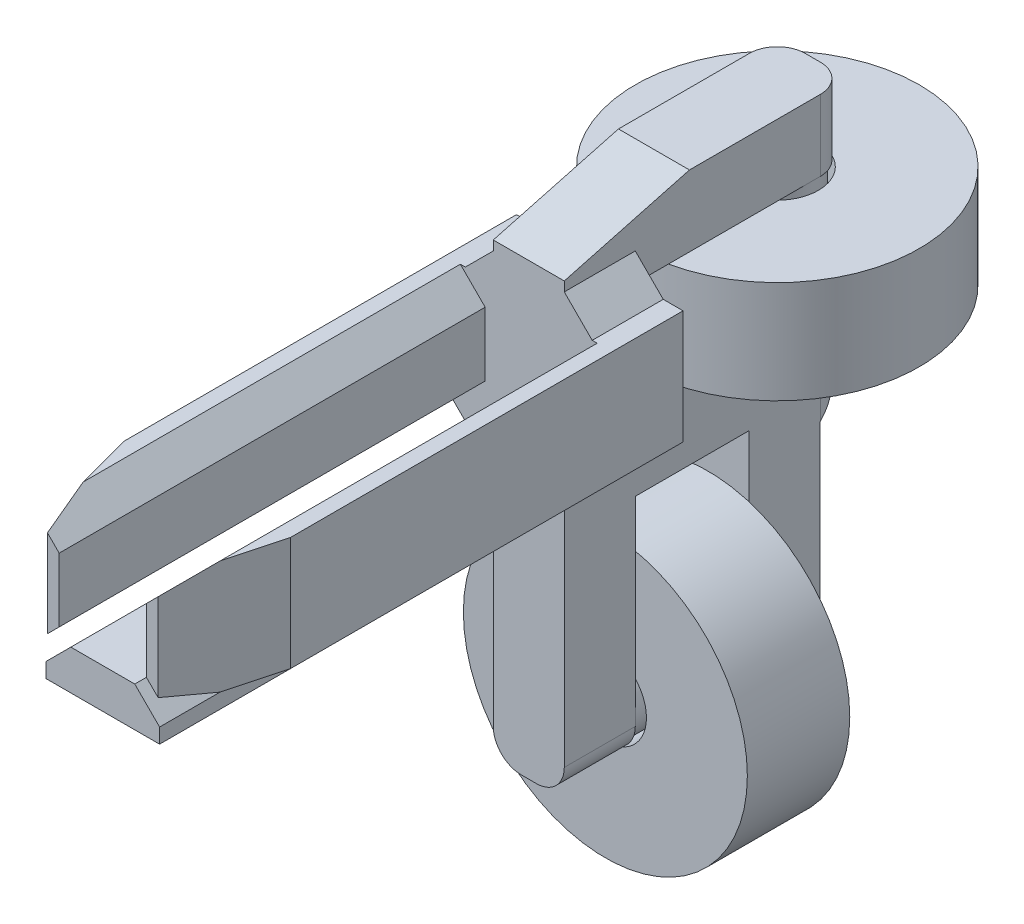
SolidWorks part; units mm, degrees
ref_plane "Front Plane" through (0, 0, 0) normal (0, 0, 1) x (1, 0, 0)
ref_plane "Top Plane" through (0, 0, 0) normal (0, 1, 0) x (1, 0, 0)
ref_plane "Right Plane" through (0, 0, 0) normal (1, 0, 0) x (0, 0, -1)
sketch "Sketch1" plane through (0, 0, 0) normal (0, 0, 1) x (1, 0, 0)
  line L1 (6.12, -5.08) -> (3.9, -2.86)
  line L2 (3.9, -2.86) -> (3.9, 2.86)
  line L3 (3.9, 2.86) -> (6.12, 5.08)
  line L5 (-6.12, -5.08) -> (-3.9, -2.86)
  line L6 (-3.9, -2.86) -> (-3.9, 2.86)
  line L7 (-3.9, 2.86) -> (-6.12, 5.08)
  line L8 (3.9, 0) -> (-3.9, 0) construction
  line L9 (0, 0) -> (-8.3021, -8.3021) construction
  line L10 (-6.12, 5.08) -> (-7.45, 5.08)
  line L12 (-6.12, -5.08) -> (-7.45, -5.08)
  line L13 (-7.45, 5.08) -> (-7.45, -5.08)
  line L14 (6.12, -5.08) -> (7.45, -5.08)
  line L16 (6.12, 5.08) -> (7.45, 5.08)
  line L17 (7.45, -5.08) -> (7.45, 5.08)
  line L18 (5.08, -7.45) -> (-5.08, -7.45)
  line L19 (-5.08, -6.12) -> (-5.08, -7.45)
  line L20 (5.08, -6.12) -> (5.08, -7.45)
  line L21 (2.86, -3.9) -> (5.08, -6.12)
  line L22 (-2.86, -3.9) -> (2.86, -3.9)
  line L23 (-5.08, -6.12) -> (-2.86, -3.9)
  dimension "D1" = 45
  dimension "D2" = 10.16
  dimension "D3" = 5.72
  dimension "D5" = 7.8
  dimension "D6" = 1.33
  dimension "D7" = 45
extrude "Boss-Extrude1" add sketch "Sketch1" along normal blind 38.1
chamfer "Chamfer1" distance 2.5 angle 75 1 edges at (7.45, 0, 38.1)
chamfer "Chamfer2" distance 2.5 angle 75 1 edges at (-7.45, 0, 38.1)
sketch "Sketch3" plane through (0, 0, 0) normal (0, 0, 1) x (1, 0, 0)
  line L0 (-7.45, -5.08) -> (-6.12, -5.08) construction
  line L1 (7.45, 5.08) -> (-7.45, 5.08)
  line L2 (7.45, 5.08) -> (7.45, -5.08)
  line L4 (-7.45, 5.08) -> (-7.45, -5.08)
  line L5 (-6.12, 5.08) -> (-7.45, 5.08) construction
  line L6 (-7.45, 5.08) -> (-7.45, -5.08) construction
  line L7 (7.45, -5.08) -> (5.08, -7.45)
  line L8 (5.08, -7.45) -> (-5.08, -7.45)
  line L9 (-5.08, -7.45) -> (-7.45, -5.08)
extrude "Boss-Extrude2" add sketch "Sketch3" against normal blind 6.35
sketch "Sketch4" plane through (0, 0, -6.35) normal (0, 0, -1) x (-1, 0, 0)
  line L0 (-3.175, 5.08) -> (3.175, 5.08)
  line L5 (-3.175, -11.43) -> (3.175, -11.43)
  line L6 (-3.175, -11.43) -> (-3.175, -5.08)
  line L7 (-3.175, 11.43) -> (3.175, 11.43)
  line L8 (3.175, -11.43) -> (3.175, -5.08)
  line L11 (-7.45, 5.08) -> (7.45, 5.08) construction
  line L12 (-3.175, -5.08) -> (3.175, -5.08)
  line L14 (-3.175, 5.08) -> (-3.175, 11.43)
  line L17 (3.175, 5.08) -> (3.175, 11.43)
  point P0 (0, 0)
  point P14 (0, 5.08)
  dimension "D1" = 6.35
extrude "Boss-Extrude3" add sketch "Sketch4" along normal blind 25.4 from surface at -6.35 starting at face at (0, -2.0883, 0)
sketch "Sketch5" plane through (0, -5.08, 0) normal (0, 1, 0) x (1, 0, 0)
  line L0 (-3.175, 25.4) -> (3.175, 25.4) construction
  line L1 (-3.175, 25.4) -> (-3.175, 0) construction
  line L2 (3.175, 25.4) -> (3.175, 0) construction
  circle A0 centre (0, 22.225) radius 3.175
extrude "Boss-Extrude4" add sketch "Sketch5" along normal up to next
sketch "Sketch6" plane through (0, -5.08, 0) normal (0, 1, 0) x (1, 0, 0)
  arc A1 (-3.175, 22.225) -> (3.175, 22.225) centre (0, 22.225) ccw construction
  circle A2 centre (0, 22.225) radius 12.7
  arc A3 (-3.175, 22.225) -> (3.175, 22.225) centre (0, 22.225) ccw construction
  circle A4 centre (0, 22.225) radius 3.675
  dimension "D1" = 0.5
  dimension "D2" = 25.4
extrude "Boss-Extrude5" add sketch "Sketch6" along normal blind 9.16 from offset 0.5
sketch "Sketch7" plane through (3.175, 0, 0) normal (1, 0, 0) x (0, 0, -1)
  line L0 (25.4, -11.43) -> (0, -11.43) construction
  line L1 (0, -11.43) -> (6.35, -11.43)
  line L2 (0, -11.43) -> (0, -31.75)
  line L3 (0, -31.75) -> (6.35, -31.75)
  line L4 (6.35, -11.43) -> (6.35, -31.75)
  line L5 (16.51, -11.43) -> (22.86, -11.43)
  line L6 (16.51, -11.43) -> (16.51, -31.75)
  line L7 (16.51, -31.75) -> (22.86, -31.75)
  line L8 (22.86, -11.43) -> (22.86, -31.75)
  line L9 (6.35, -11.43) -> (16.51, -11.43) construction
  line L10 (6.35, -5.08) -> (6.35, 5.08) construction
  dimension "D1" = 6.35
  dimension "D2" = 31.75
extrude "Boss-Extrude6" add sketch "Sketch7" against normal up to surface (6.35 mm away) up to face at (-3.175, -7.5714, -12.2464)
sketch "Sketch8" plane through (0, 0, -16.51) normal (0, 0, 1) x (1, 0, 0)
  line L0 (3.175, -7.45) -> (3.175, -31.75) construction
  line L1 (-3.175, -31.75) -> (-3.175, -7.45) construction
  line L2 (-3.175, -31.75) -> (3.175, -31.75) construction
  circle A0 centre (0, -28.575) radius 3.175
extrude "Boss-Extrude7" add sketch "Sketch8" along normal up to next
sketch "Sketch9" plane through (0, 0, -16.51) normal (0, 0, 1) x (1, 0, 0)
  circle A0 centre (0, -28.575) radius 3.675
  circle A1 centre (0, -28.575) radius 12.7
  arc A2 (3.175, -28.575) -> (-3.175, -28.575) centre (0, -28.575) ccw construction
  arc A3 (3.175, -28.575) -> (-3.175, -28.575) centre (0, -28.575) ccw construction
  dimension "D1" = 0.5
  dimension "D2" = 25.4
extrude "Boss-Extrude8" add sketch "Sketch9" along normal blind 9.16 from offset 0.5 separate body
chamfer "Chamfer3" distance 2.5 angle 45 3 edges at (3.175, 5.08, -3.175) (-3.175, 5.08, -3.175) (0, -11.43, -22.86)
fillet "Fillet1" radius 2.5 8 edges at (-3.175, -8.255, -25.4) (3.175, -8.255, -25.4) (-3.175, 8.255, -25.4) (3.175, 8.255, -25.4) (-3.175, -31.75, -3.175) (3.175, -31.75, -3.175) (-3.175, -31.75, -19.685) (3.175, -31.75, -19.685)
chamfer "Chamfer4" distance 3 angle 75 1 edges at (0, 11.43, 0)
